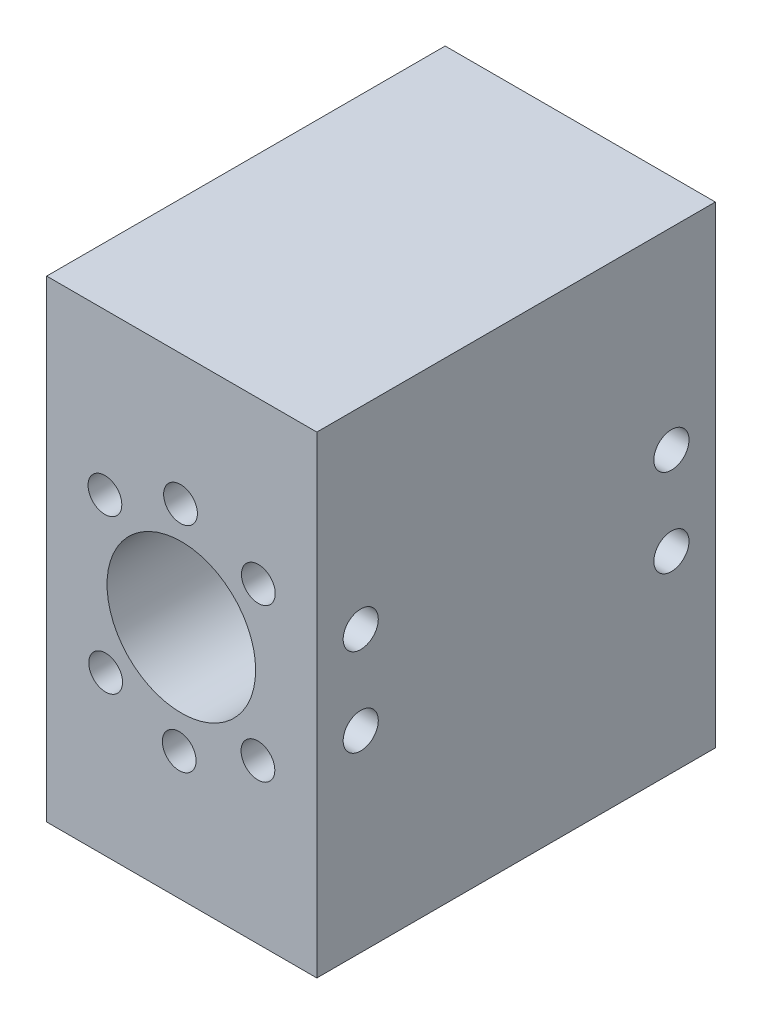
SolidWorks part; units mm, degrees
ref_plane "Front Plane" through (0, 0, 0) normal (0, 0, 1) x (1, 0, 0)
ref_plane "Top Plane" through (0, 0, 0) normal (0, 1, 0) x (1, 0, 0)
ref_plane "Right Plane" through (0, 0, 0) normal (1, 0, 0) x (0, 0, -1)
sketch "Sketch1" plane through (0, 0, 0) normal (0, 0, 1) x (1, 0, 0)
  line L0 (0.0608, 20.3128) -> (0.0608, -20.1872) construction
  line L1 (-14.9392, 0.0628) -> (15.0608, 0.0628) construction
  line L2 (-14.9392, 13.6666) -> (-14.9392, -13.541)
  line L3 (15.0608, 13.6666) -> (15.0608, -13.541)
  line L4 (0.0608, 20.3128) -> (0.0608, 35.0628) construction
  line L5 (-19.9392, 35.0628) -> (20.0608, 35.0628)
  line L6 (-19.9392, 35.0628) -> (-19.9392, -34.9372)
  line L7 (-19.9392, -34.9372) -> (20.0608, -34.9372)
  line L8 (20.0608, 35.0628) -> (20.0608, -34.9372)
  line L9 (-19.9392, 35.0628) -> (20.0608, -34.9372) construction
  line L10 (-19.9392, -34.9372) -> (20.0608, 35.0628) construction
  line L11 (0.0608, 0.0628) -> (20.0608, 0.0628) construction
  arc A0 (-14.9392, -13.541) -> (15.0608, -13.541) centre (0.0608, 0.0628) ccw
  arc A1 (15.0608, 13.6666) -> (-14.9392, 13.6666) centre (0.0608, 0.0628) ccw
  dimension "D1" = 40.5
  dimension "D2" = 30
  dimension "D3" = 20
  dimension "D4" = 35
sketch "Sketch2" plane through (0, 0, 0) normal (0, 0, 1) x (1, 0, 0)
  line L0 (0, -20.25) -> (0, 20.25) construction
  line L2 (15, 0) -> (-15, 0) construction
  line L6 (0, 0) -> (11.3137, -11.3137) construction
  circle A2 centre (0, 0) radius 11
  circle A3 centre (-11.3137, 11.3137) radius 2.5
  circle A4 centre (-0.1223, 15.7597) radius 2.5
  circle A5 centre (11.4027, 11.2637) radius 2.5
  circle A6 centre (11.3394, -11.4064) radius 2.5
  circle A7 centre (-0.3123, -16.0291) radius 2.5
  circle A8 centre (-11.2041, -11.4064) radius 2.5
  point P0 (0, -16)
  point P2 (11.3137, -11.3137)
  point P30 (-11.3137, -11.3137)
  point P32 (-11.3137, 11.3137)
  point P33 (0, 16)
  point P34 (11.3137, 11.3137)
  dimension "D2" = 45
  dimension "D3" = 16
extrude "Boss-Extrude1" add sketch "Sketch1" along normal blind 59 contours L5 L8 L7 L6
extrude "Cut-Extrude1" cut sketch "Sketch2" along normal through all
sketch "Sketch5" plane through (-19.9392, 0, 0) normal (-1, 0, 0) x (0, 0, 1)
  line L0 (67.7715, 0.0628) -> (-8.7715, 0.0628) construction
  line L2 (29.5, 35.0628) -> (29.5, -34.9372) construction
  line L5 (29.5, 35.0628) -> (29.5, -34.9372) construction
  line L6 (59, 35.0628) -> (0, 35.0628) construction
  line L7 (59, -34.9372) -> (0, -34.9372) construction
  line L8 (0, 0.0628) -> (59, 0.0628) construction
  line L9 (0, 35.0628) -> (0, -34.9372) construction
  line L10 (59, 35.0628) -> (59, -34.9372) construction
  circle A0 centre (29.5, 0.0628) radius 2.5
  circle A1 centre (39.5, 0.0628) radius 2.5
  circle A2 centre (19.5, 0.0628) radius 2.5
  circle A3 centre (29.5, 10.0628) radius 2.5
  circle A4 centre (29.5, -9.9372) radius 2.5
  point P28 (29.5, 0.0628)
  dimension "D1" = 10
  dimension "D2" = 10
  dimension "D3" = 10
  dimension "D4" = 10
extrude "Cut-Extrude3" cut sketch "Sketch5" against normal blind 5
sketch "Sketch7" plane through (20.0608, 0, 0) normal (1, 0, 0) x (0, 0, -1)
  line L0 (0, 0) -> (-59, 0.0628) construction
  line L1 (-29.5, 35.0628) -> (-29.5, -34.9372) construction
  line L2 (-59, 35.0628) -> (-59, -34.9372) construction
  line L3 (-29.5006, 0.03) -> (-29.5006, -17.47) construction
  line L4 (-59, 35.0628) -> (0, 35.0628) construction
  line L5 (-59, -34.9372) -> (0, -34.9372) construction
  line L6 (-59.5006, 0.03) -> (0.4994, 0.03) construction
  point P6 (-6.5006, 6.53)
  point P12 (-52.5006, 6.53)
  point P17 (-6.5006, -6.47)
  point P18 (-52.5006, -6.47)
hole_wizard "Tap Drill for M5 Helicoil1" positions "Sketch8" profile "Sketch9" hole size "M5x0.8" standard "ANSI Metric"
sketch "Sketch8" plane through (20.0608, 0, 0) normal (1, 0, 0) x (0, 0, -1)
  point P0 (-52.5006, 6.53)
  point P3 (-52.5006, -6.47)
  point P6 (-6.5006, -6.47)
  point P9 (-6.5006, 6.53)
sketch "Sketch9" plane through (20.0608, 6.53, 52.5006) normal (0, 1, 0) x (0, 0, -1)
  line L0 (0, 0) -> (0, 8)
  line L1 (0, 8) -> (2.6, 6.4378)
  line L2 (2.6, 6.4378) -> (2.6, 0)
  line L5 (2.6, 0) -> (0, 0)
  line L10 (0, 8) -> (-2.6, 6.4378) construction
  line L11 (0, -6.35) -> (0, 107.95) construction
  dimension "Hole Dia." = 5.2
  dimension "Hole Depth" = 8
  dimension "Drill Angle" = 118
